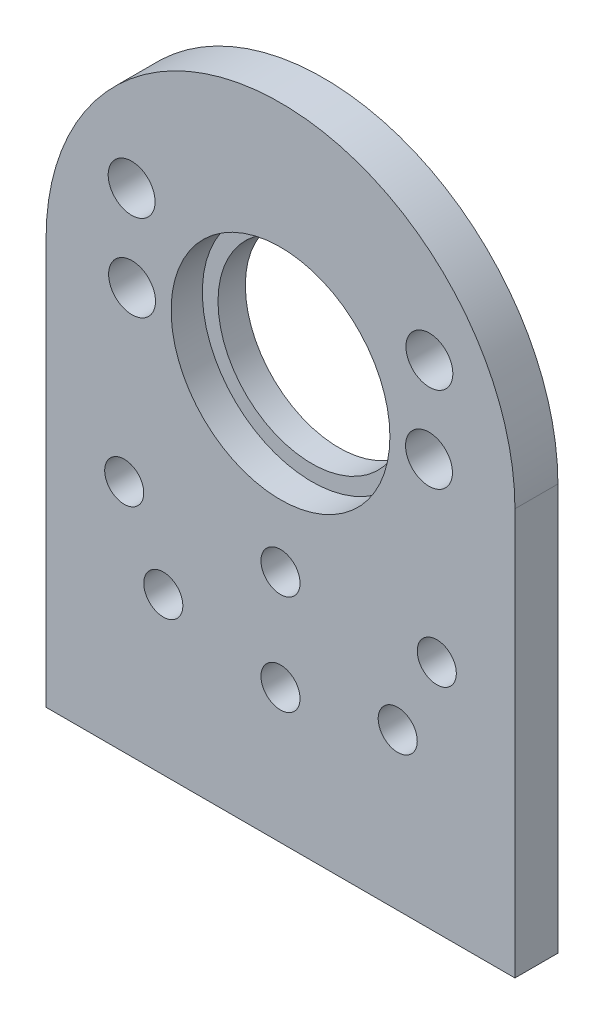
SolidWorks part; units mm, degrees
ref_plane "Front Plane" through (0, 0, 0) normal (0, 0, 1) x (1, 0, 0)
ref_plane "Top Plane" through (0, 0, 0) normal (0, 1, 0) x (1, 0, 0)
ref_plane "Right Plane" through (0, 0, 0) normal (1, 0, 0) x (0, 0, -1)
sketch "Sketch1" plane through (0, 0, 0) normal (0, 0, 1) x (1, 0, 0)
  line L0 (0, 0) -> (15, -13) construction
  line L2 (-15, 13) -> (-15, -13)
  line L3 (-15, -13) -> (15, -13)
  line L4 (15, 13) -> (15, -13)
  line L5 (-15, 13) -> (0, 0) construction
  line L6 (-15, -13) -> (15, 13) construction
  line L7 (-7.5, -3) -> (7.5, -3) construction
  line L8 (-10, 2) -> (10, 2) construction
  arc A0 (15, 13) -> (-15, 13) centre (0, 13) ccw
  circle A1 centre (0, 13) radius 6
  circle A2 centre (0, 13) radius 9.5 construction
  circle A3 centre (-9.5, 13) radius 1.5
  circle A4 centre (9.5, 13) radius 1.5
  circle A5 centre (-7.5, -3) radius 1.25
  circle A6 centre (7.5, -3) radius 1.25
  circle A7 centre (10, 2) radius 1.25
  circle A8 centre (-10, 2) radius 1.25
  circle A9 centre (0, 2) radius 1.25
  circle A10 centre (0, -4.4) radius 1.25
  point P0 (0, 0)
  dimension "D3" = 15
  dimension "D4" = 12
  dimension "D5" = 13
  dimension "D6" = 19
  dimension "D7" = 3
  dimension "D8" = 11
  dimension "D9" = 16
  dimension "D14" = 2.5
  dimension "D15" = 2.5
  dimension "D16" = 6.4
  dimension "D17" = 5
  dimension "D18" = 2.5
  dimension "D19" = 2.5
  dimension "D1" = 30
  dimension "D2" = 26
  dimension "D10" = 15
  dimension "D11" = 7.5
  dimension "D12" = 20
  dimension "D13" = 10
extrude "Boss-Extrude1" add sketch "Sketch1" along normal blind 3.75
sketch "Sketch2" plane through (0, 0, 3.75) normal (0, 0, 1) x (1, 0, 0)
  circle A0 centre (0, 13) radius 7
  dimension "D1" = 14
extrude "Cut-Extrude1" cut sketch "Sketch2" against normal blind 2
sketch "Sketch3" plane through (0, 0, 0) normal (0, 0, 1) x (1, 0, 0)
  line L0 (-13.5, 13) -> (-13.5, -11.5)
  line L1 (-13.5, -11.5) -> (13.5, -11.5)
  line L2 (13.5, -11.5) -> (13.5, 13)
  line L3 (15, -13) -> (15, 13)
  line L4 (-15, 13) -> (-15, -13)
  line L5 (-15, -13) -> (15, -13)
  line L6 (15, -13) -> (15, 13)
  line L7 (-15, 13) -> (-15, -13)
  line L8 (-15, -13) -> (15, -13)
  arc A0 (13.5, 13) -> (-13.5, 13) centre (0, 13) ccw
  arc A1 (15, 13) -> (-15, 13) centre (0, 13) ccw
  arc A2 (15, 13) -> (-15, 13) centre (0, 13) ccw
  dimension "D1" = 0
  dimension "D2" = 1.5
extrude "Cut-Extrude2" cut sketch "Sketch3" along normal blind 1
sketch "Sketch4" plane through (0, 0, 3.75) normal (0, 0, 1) x (1, 0, 0)
  line L0 (0, 13) -> (-9.5, 13) construction
  line L1 (0, 13) -> (-9.5263, 18.5) construction
  line L2 (0, 13) -> (0, 17.4111) construction
  circle A0 centre (-9.5263, 18.5) radius 1.5
  circle A1 centre (9.5263, 18.5) radius 1.5
  dimension "D3" = 3
  dimension "D1" = 30
  dimension "D2" = 11
extrude "Cut-Extrude3" cut sketch "Sketch4" against normal blind 10
